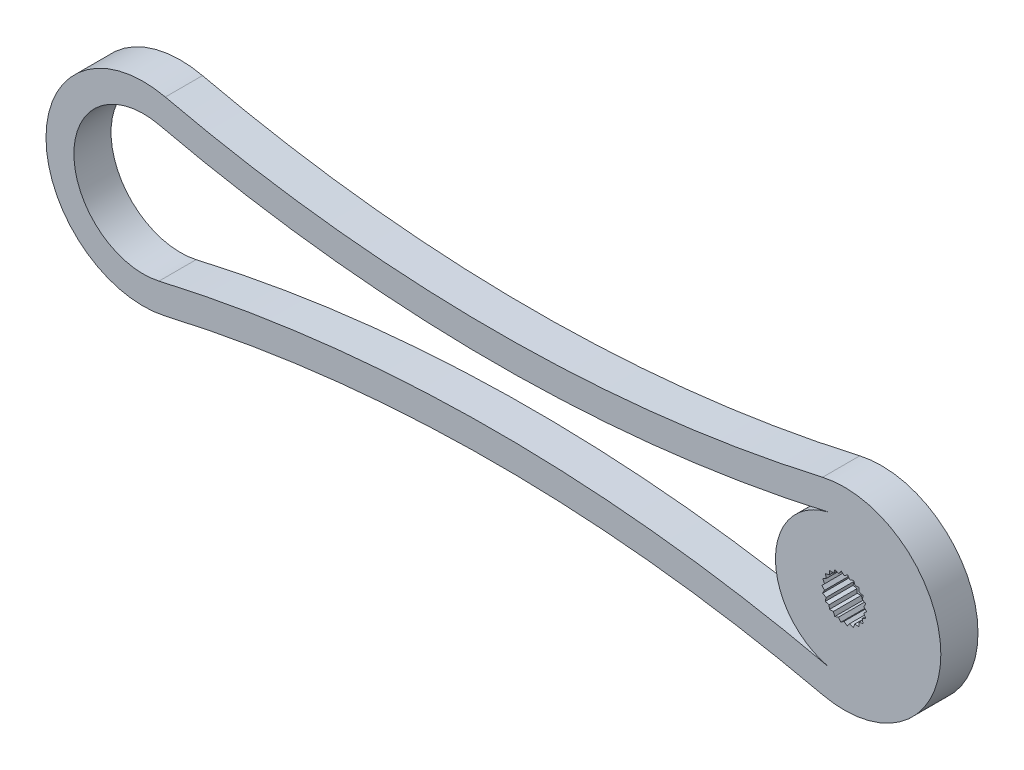
SolidWorks part; units mm, degrees
ref_plane "Ebene oben" through (0, 0, 0) normal (0, 0, 1) x (1, 0, 0)
ref_plane "Ebene rechts" through (0, 0, 0) normal (0, 1, 0) x (1, 0, 0)
ref_plane "Ebene vorne" through (0, 0, 0) normal (1, 0, 0) x (0, 0, -1)
sketch "Skizze1" plane through (0, 0, 0) normal (0, 0, 1) x (1, 0, 0)
  line L0 (0, 0) -> (-75.4459, 0) construction
  arc A0 (-73.0816, 10.2092) -> (-73.0816, -10.2092) centre (-75.4459, 0) ccw
  arc A1 (-2.327, -10.1393) -> (-2.327, 10.1393) centre (0, 0) ccw
  circle A2 centre (0, 0) radius 1
  arc A3 (-2.327, 10.1393) -> (-73.0816, 10.2092) centre (-37.5526, 163.6237) cw
  arc A4 (-2.327, -10.1393) -> (-73.0816, -10.2092) centre (-37.5526, -163.6237) ccw
  dimension "D2" = 2
  dimension "D3" = 10.4029
  dimension "D4" = 157.4748
  dimension "D5" = 10.4794
  dimension "D1" = 75.4459
extrude "Aufsatz-Linear austragen1" add sketch "Skizze1" along normal blind 4
sketch "Skizze2" plane through (0, 0, 4) normal (0, 0, 1) x (1, 0, 0)
  arc A4 (-1.6559, 7.2153) -> (-1.6559, -7.2153) centre (0, 0) ccw
  arc A8 (-73.7584, 7.2866) -> (-1.6559, 7.2153) centre (-37.5526, 163.6237) ccw
  arc A9 (-73.7584, 7.2866) -> (-73.7584, -7.2866) centre (-75.4459, 0) ccw
  arc A10 (-1.6559, -7.2153) -> (-73.7584, -7.2866) centre (-37.5526, -163.6237) ccw
  arc A11 (-1.6559, -7.2153) -> (-1.6559, 7.2153) centre (0, 0) ccw
  arc A12 (-73.7584, 7.2866) -> (-1.6559, 7.2153) centre (-37.5526, 163.6237) ccw
  arc A13 (-73.7584, 7.2866) -> (-73.7584, -7.2866) centre (-75.4459, 0) ccw
  arc A14 (-1.6559, -7.2153) -> (-73.7584, -7.2866) centre (-37.5526, -163.6237) ccw
  dimension "D1" = 3
extrude "Schnitt-Linear austragen1" cut sketch "Skizze2" against normal blind 6
sketch "Skizze6" plane through (0, 0, 4) normal (0, 0, 1) x (1, 0, 0)
  circle A0 centre (0, 0) radius 1 construction
  point P0 (0, 0)
  line B0 (1.8333, 0.8229) -> (1.9218, 1.2175)
  line B1 (2.187, 0.6267) -> (1.8333, 0.8229)
  line B2 (1.9908, 0.273) -> (2.187, 0.6267)
  line B3 (2.275, -0.0148) -> (1.9908, 0.273)
  line B4 (1.9871, -0.2989) -> (2.275, -0.0148)
  line B5 (2.1786, -0.6551) -> (1.9871, -0.2989)
  line B6 (1.8224, -0.8466) -> (2.1786, -0.6551)
  line B7 (1.9058, -1.2424) -> (1.8224, -0.8466)
  line B8 (1.5101, -1.3258) -> (1.9058, -1.2424)
  line B9 (1.4786, -1.729) -> (1.5101, -1.3258)
  line B10 (1.0754, -1.6975) -> (1.4786, -1.729)
  line B11 (0.9316, -2.0755) -> (1.0754, -1.6975)
  line B12 (0.5536, -1.9317) -> (0.9316, -2.0755)
  line B13 (0.3091, -2.2539) -> (0.5536, -1.9317)
  line B14 (-0.0131, -2.0094) -> (0.3091, -2.2539)
  line B15 (-0.3384, -2.2497) -> (-0.0131, -2.0094)
  line B16 (-0.5787, -1.9244) -> (-0.3384, -2.2497)
  line B17 (-0.9585, -2.0632) -> (-0.5787, -1.9244)
  line B18 (-1.0974, -1.6834) -> (-0.9585, -2.0632)
  line B19 (-1.5009, -1.7096) -> (-1.0974, -1.6834)
  line B20 (-1.5272, -1.306) -> (-1.5009, -1.7096)
  line B21 (-1.9218, -1.2175) -> (-1.5272, -1.306)
  line B22 (-1.8333, -0.8229) -> (-1.9218, -1.2175)
  line B23 (-2.187, -0.6267) -> (-1.8333, -0.8229)
  line B24 (-1.9908, -0.273) -> (-2.187, -0.6267)
  line B25 (-2.275, 0.0148) -> (-1.9908, -0.273)
  line B26 (-1.9871, 0.2989) -> (-2.275, 0.0148)
  line B27 (-2.1786, 0.6551) -> (-1.9871, 0.2989)
  line B28 (-1.8224, 0.8466) -> (-2.1786, 0.6551)
  line B29 (-1.9058, 1.2424) -> (-1.8224, 0.8466)
  line B30 (-1.5101, 1.3258) -> (-1.9058, 1.2424)
  line B31 (-1.4786, 1.729) -> (-1.5101, 1.3258)
  line B32 (-1.0754, 1.6975) -> (-1.4786, 1.729)
  line B33 (-0.9316, 2.0755) -> (-1.0754, 1.6975)
  line B34 (-0.5536, 1.9317) -> (-0.9316, 2.0755)
  line B35 (-0.3091, 2.2539) -> (-0.5536, 1.9317)
  line B36 (0.0131, 2.0094) -> (-0.3091, 2.2539)
  line B37 (0.3384, 2.2497) -> (0.0131, 2.0094)
  line B38 (0.5787, 1.9244) -> (0.3384, 2.2497)
  line B39 (0.9585, 2.0632) -> (0.5787, 1.9244)
  line B40 (1.0974, 1.6834) -> (0.9585, 2.0632)
  line B41 (1.5009, 1.7096) -> (1.0974, 1.6834)
  line B42 (1.5272, 1.306) -> (1.5009, 1.7096)
  line B43 (1.9218, 1.2175) -> (1.5272, 1.306)
  line B44 (-0.9316, 2.0755) -> (0.9316, -2.0755) construction
  line B45 (-1.8333, -0.8229) -> (1.8333, 0.8229) construction
  line B46 (1.1656, 1.788) -> (1.0181, 2.1915)
  line B47 (1.0181, 2.1915) -> (0.6146, 2.044)
  line B48 (0.6146, 2.044) -> (0.3594, 2.3895)
  line B49 (0.3594, 2.3895) -> (0.0139, 2.1343)
  line B50 (0.0139, 2.1343) -> (-0.3283, 2.394)
  line B51 (-0.3283, 2.394) -> (-0.588, 2.0518)
  line B52 (-0.588, 2.0518) -> (-0.9895, 2.2045)
  line B53 (-0.9895, 2.2045) -> (-1.1422, 1.803)
  line B54 (-1.1422, 1.803) -> (-1.5705, 1.8365)
  line B55 (-1.5705, 1.8365) -> (-1.6039, 1.4082)
  line B56 (-1.6039, 1.4082) -> (-2.0243, 1.3196)
  line B57 (-2.0243, 1.3196) -> (-1.9357, 0.8993)
  line B58 (-1.9357, 0.8993) -> (-2.3141, 0.6958)
  line B59 (-2.3141, 0.6958) -> (-2.1106, 0.3175)
  line B60 (-2.1106, 0.3175) -> (-2.4164, 0.0157)
  line B61 (-2.4164, 0.0157) -> (-2.1146, -0.29)
  line B62 (-2.1146, -0.29) -> (-2.3229, -0.6657)
  line B63 (-2.3229, -0.6657) -> (-1.9472, -0.874)
  line B64 (-1.9472, -0.874) -> (-2.0413, -1.2932)
  line B65 (-2.0413, -1.2932) -> (-1.6221, -1.3872)
  line B66 (-1.6221, -1.3872) -> (-1.5943, -1.8159)
  line B67 (-1.5943, -1.8159) -> (-1.1656, -1.788)
  line B68 (-1.1656, -1.788) -> (-1.0181, -2.1915)
  line B69 (-1.0181, -2.1915) -> (-0.6146, -2.044)
  line B70 (-0.6146, -2.044) -> (-0.3594, -2.3895)
  line B71 (-0.3594, -2.3895) -> (-0.0139, -2.1343)
  line B72 (-0.0139, -2.1343) -> (0.3283, -2.394)
  line B73 (0.3283, -2.394) -> (0.588, -2.0518)
  line B74 (0.588, -2.0518) -> (0.9895, -2.2045)
  line B75 (0.9895, -2.2045) -> (1.1422, -1.803)
  line B76 (1.1422, -1.803) -> (1.5705, -1.8365)
  line B77 (1.5705, -1.8365) -> (1.6039, -1.4082)
  line B78 (1.6039, -1.4082) -> (2.0243, -1.3196)
  line B79 (2.0243, -1.3196) -> (1.9357, -0.8993)
  line B80 (1.9357, -0.8993) -> (2.3141, -0.6958)
  line B81 (2.3141, -0.6958) -> (2.1106, -0.3175)
  line B82 (2.1106, -0.3175) -> (2.4164, -0.0157)
  line B83 (2.4164, -0.0157) -> (2.1146, 0.29)
  line B84 (2.1146, 0.29) -> (2.3229, 0.6657)
  line B85 (2.3229, 0.6657) -> (1.9472, 0.874)
  line B86 (1.9472, 0.874) -> (2.0413, 1.2932)
  line B87 (2.0413, 1.2932) -> (1.6221, 1.3872)
  line B88 (1.6221, 1.3872) -> (1.5943, 1.8159)
  line B89 (1.5943, 1.8159) -> (1.1656, 1.788)
  circle M95 centre (0, 0) radius 1
sketch_block_instance "Block1-1"
sketch_block "Block1"
extrude "Schnitt-Linear austragen2" cut sketch "Skizze6" against normal blind 3 contours B0 B43 B42 B41 B40 B39 B38 B37 B36 B35 B34 B33 B32 B31 B30 B29 B28 B27 B26 B25 B24 B23 B22 B21 B20 B19 B18 B17 B16 B15 B14 B13 B12 B11 B10 B9 B8 B7 B6 B5 B4 B3 B2 B1 M95 | B88 B89 B46 B47 B48 B49 B50 B51 B52 B53 B54 B55 B56 B57 B58 B59 B60 B61 B62 B63 B64 B65 B66 B67 B68 B69 B70 B71 B72 B73 B74 B75 B76 B77 B78 B79 B80 B81 B82 B83 B84 B85 B86 B87 B43 B0 B1 B2 B3 B4
